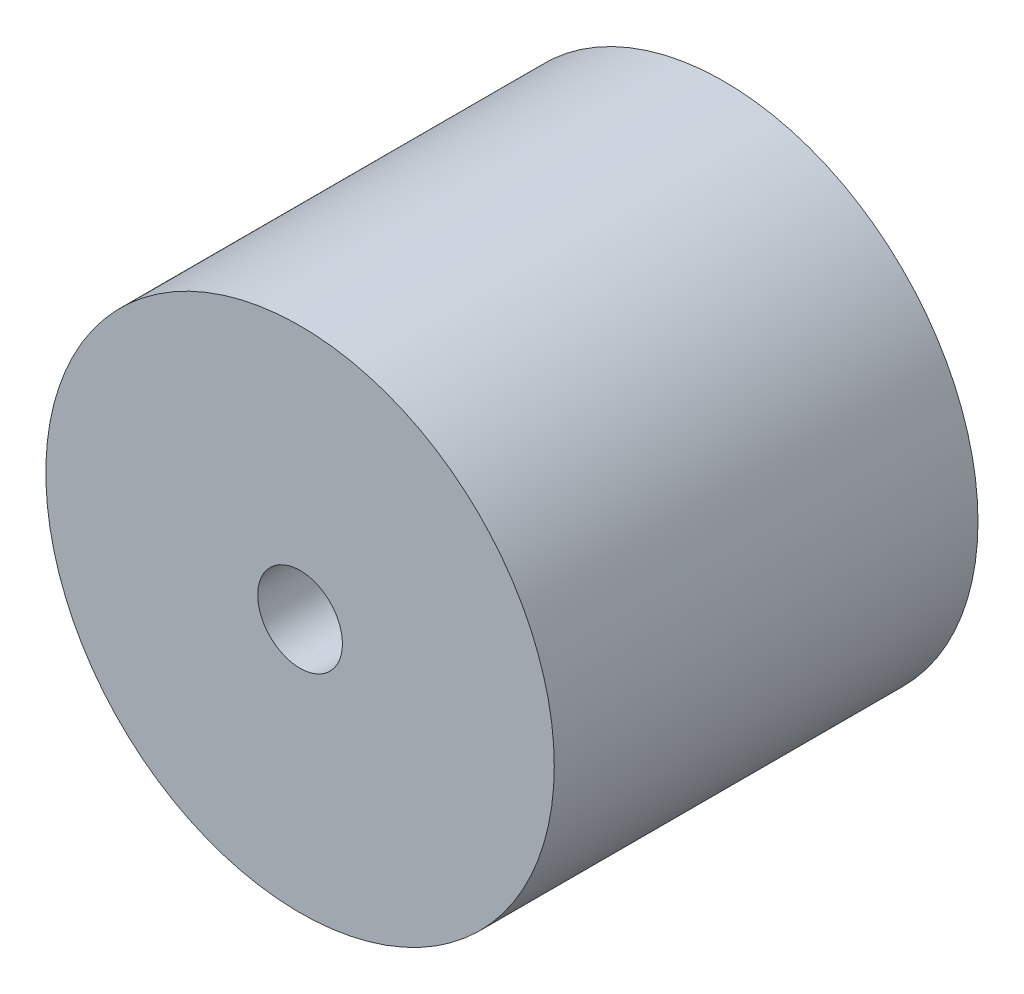
SolidWorks part; units mm, degrees
ref_plane "Front Plane" through (0, 0, 0) normal (0, 0, 1) x (1, 0, 0)
ref_plane "Top Plane" through (0, 0, 0) normal (0, 1, 0) x (1, 0, 0)
ref_plane "Right Plane" through (0, 0, 0) normal (1, 0, 0) x (0, 0, -1)
sketch "Sketch1" plane through (0, 0, 0) normal (0, 0, 1) x (1, 0, 0)
  circle A0 centre (0, 0) radius 18
  dimension "D1" = 36
extrude "Boss-Extrude1" add sketch "Sketch1" along normal blind 30
sketch "Sketch2" plane through (0, 0, 30) normal (0, 0, 1) x (1, 0, 0)
  circle A0 centre (0, 0) radius 3
  dimension "D1" = 6
extrude "Cut-Extrude1" cut sketch "Sketch2" against normal through all
